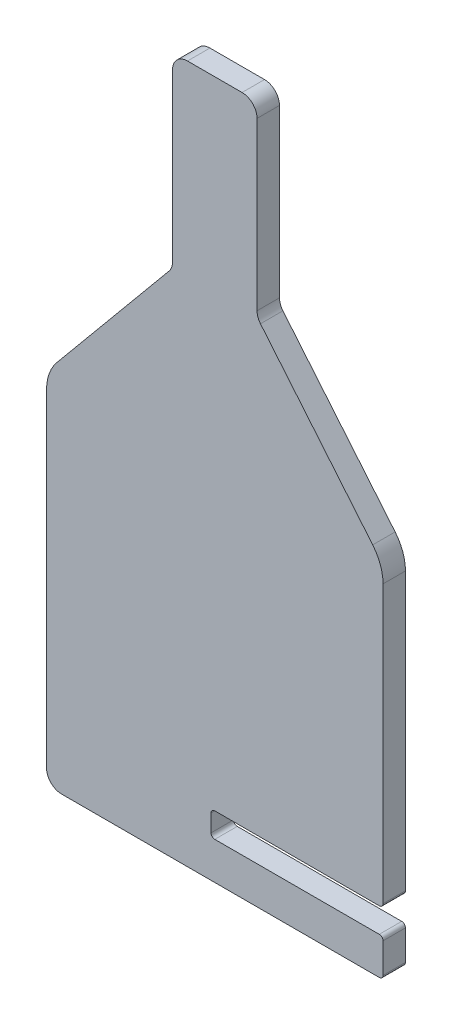
SolidWorks part; units mm, degrees
ref_plane "Alzado" through (0, 0, 0) normal (0, 0, 1) x (1, 0, 0)
ref_plane "Planta" through (0, 0, 0) normal (0, 1, 0) x (1, 0, 0)
ref_plane "Vista lateral" through (0, 0, 0) normal (1, 0, 0) x (0, 0, -1)
sketch "Croquis1" plane through (0, 0, 0) normal (0, 0, 1) x (1, 0, 0)
  line L0 (-5.65, 20) -> (-22.5, -0.3233)
  line L1 (-5.65, 45) -> (5.65, 45)
  line L2 (-22.5, -0.3233) -> (-22.5, -48.3233)
  line L3 (-22.5, -48.3233) -> (22.5, -48.3233)
  line L4 (22.5, -0.3233) -> (22.5, -48.3233)
  line L5 (-5.65, 45) -> (5.65, 45)
  line L6 (-5.65, 45) -> (-5.65, 20)
  line L8 (5.65, 45) -> (5.65, 19.9991)
  line L9 (5.65, 19.9991) -> (22.5, -0.3233)
  line L10 (0, 75.1867) -> (0, -77.6145) construction
  dimension "D1" = 45
  dimension "D2" = 25
  dimension "D3" = 5.65
  dimension "D4" = 22.5
  dimension "D5" = 45
  dimension "D6" = 5.65
  dimension "D7" = 26.3993
  dimension "D8" = 26.4
  dimension "D9" = 48
  dimension "D10" = 48
extrude "Saliente-Extruir1" add sketch "Croquis1" along normal blind 3 contours L6 L0 L2 L3 L4 L9 L8 L1
sketch "Croquis3" plane through (0, 0, 3) normal (0, 0, 1) x (1, 0, 0)
  line L0 (22.5, -0.3233) -> (22.5, -48.3233) construction
  line L1 (22.5, -40.0233) -> (-0.5, -40.0233)
  line L2 (22.5, -40.0233) -> (22.5, -43.3233)
  line L3 (22.5, -43.3233) -> (-0.5, -43.3233)
  line L4 (-0.5, -40.0233) -> (-0.5, -43.3233)
  line L5 (-22.5, -48.3233) -> (22.5, -48.3233) construction
  dimension "D1" = 3.3
  dimension "D2" = 5
  dimension "D3" = 23
extrude "Cortar-Extruir2" cut sketch "Croquis3" against normal up to surface (3 mm away) up to face at (0, 4.0882, 0)
fillet "Redondeo1" radius 2 5 edges at (-22.5, -48.3233, 1.5) (-5.65, 20, 1.5) (-5.65, 45, 1.5) (5.65, 19.9991, 1.5) (5.65, 45, 1.5)
fillet "Redondeo2" radius 6 2 edges at (-22.5, -0.3233, 1.5) (22.5, -0.3233, 1.5)
fillet "Redondeo3" radius 0.5 5 edges at (-0.5, -40.0233, 1.5) (-0.5, -43.3233, 1.5) (22.5, -48.3233, 1.5) (22.5, -43.3233, 1.5) (22.5, -40.0233, 1.5)
